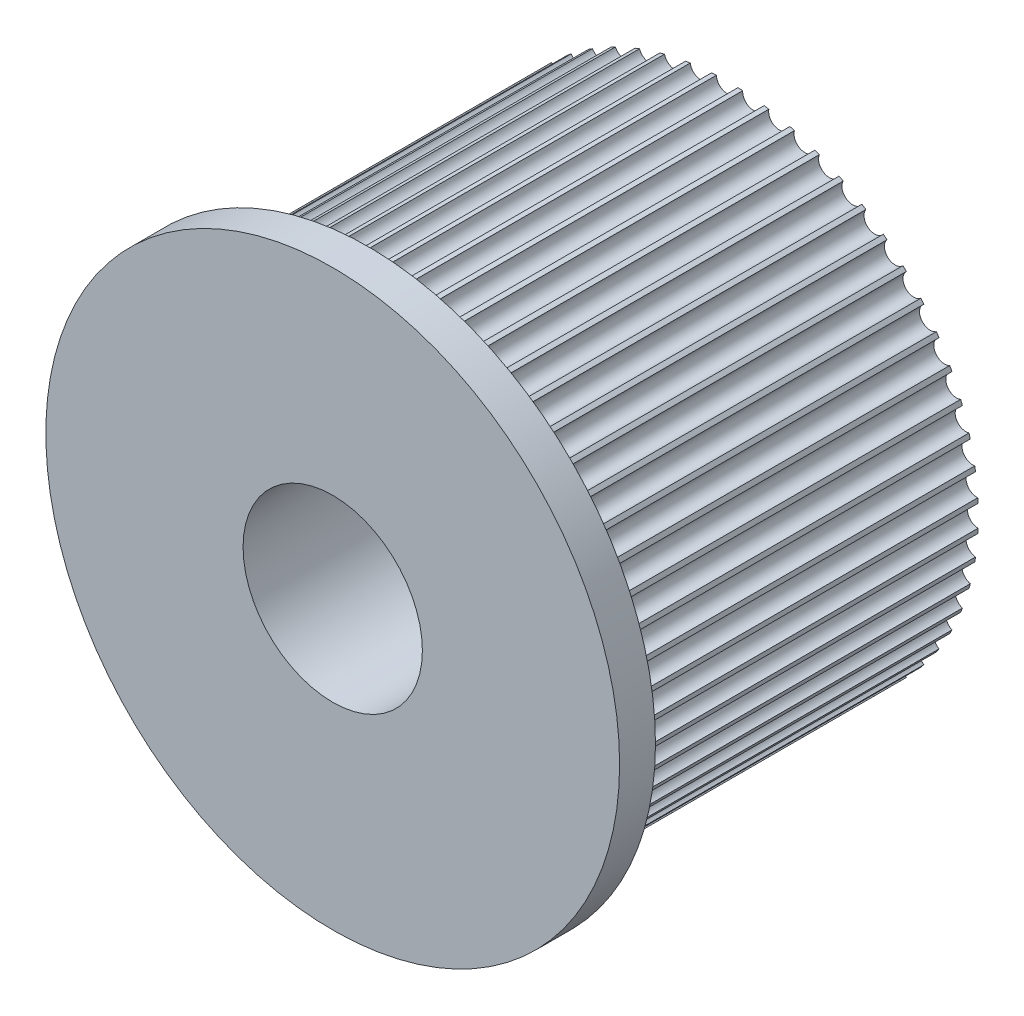
SolidWorks part; units mm, degrees
ref_plane "Front Plane" through (0, 0, 0) normal (0, 0, 1) x (1, 0, 0)
ref_plane "Top Plane" through (0, 0, 0) normal (0, 1, 0) x (1, 0, 0)
ref_plane "Right Plane" through (0, 0, 0) normal (1, 0, 0) x (0, 0, -1)
sketch "Sketch1" plane through (0, 0, 0) normal (0, 0, 1) x (1, 0, 0)
  circle A0 centre (0, 0) radius 7
extrude "Boss-Extrude1" add sketch "Sketch1" along normal blind 10
sketch "Sketch2" plane through (0, 0, 10) normal (0, 0, 1) x (1, 0, 0)
  circle A0 centre (0, 0) radius 8
extrude "Boss-Extrude2" add sketch "Sketch2" along normal blind 1
sketch "Sketch3" plane through (0, 0, 0) normal (0, 0, -1) x (-1, 0, 0)
  circle A0 centre (0, 0) radius 2.5
extrude "Cut-Extrude1" cut sketch "Sketch3" against normal blind 17 contours A0
sketch "Sketch4" plane through (0, 0, 0) normal (0, 0, -1) x (-1, 0, 0)
  line L0 (0, 8.6217) -> (0, 0) construction
  circle A0 centre (0, 7) radius 0.3
  circle A1 centre (0, 0) radius 7 construction
extrude "Cut-Extrude2" cut sketch "Sketch4" against normal blind 10
sketch "Sketch5" plane through (0, 0, 0) normal (0, 0, -1) x (-1, 0, 0)
  line L0 (0, -7) -> (0, 8) construction
  arc A0 (-0.2999, 6.9936) -> (0.2999, 6.9936) centre (0, 0) ccw construction
  circle A1 centre (0, 0) radius 8 construction
pattern_circular "CirPattern1" count 60 every 6 about axis through (0, 0, 0) along (0, 0, 1) of "Cut-Extrude2"
